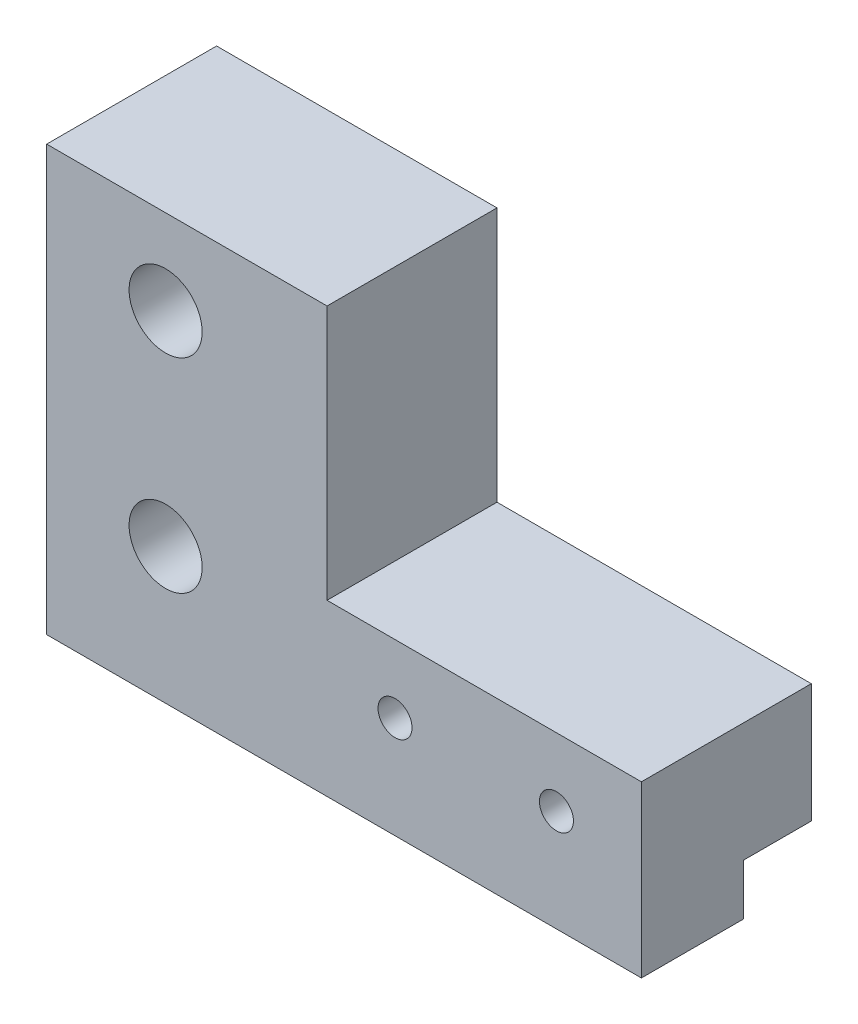
SolidWorks part; units mm, degrees
ref_plane "Front Plane" through (0, 0, 0) normal (0, 0, 1) x (1, 0, 0)
ref_plane "Top Plane" through (0, 0, 0) normal (0, 1, 0) x (1, 0, 0)
ref_plane "Right Plane" through (0, 0, 0) normal (1, 0, 0) x (0, 0, -1)
sketch "Sketch1" plane through (0, 0, 0) normal (0, 0, 1) x (1, 0, 0)
  line L0 (21, 5) -> (37.5, 5)
  line L1 (-37.5, 5) -> (-21, 5)
  line L2 (-37.5, 5) -> (-37.5, -20)
  line L3 (-37.5, -20) -> (37.5, -20)
  line L4 (37.5, 5) -> (37.5, -20)
  line L5 (-21, 5) -> (21, 5) construction
  line L6 (-21, 5) -> (-21, -10)
  line L7 (-21, -10) -> (21, -10)
  line L8 (21, 5) -> (21, -10)
  line L9 (30.5, -12) -> (30.5, 0) construction
  line L10 (30.5, 0) -> (-30.5, 0) construction
  line L11 (-30.5, 0) -> (-30.5, -12) construction
  line L12 (-30.5, -12) -> (30.5, -12) construction
  line L13 (-30.5, 0) -> (30.5, -12) construction
  line L14 (0, -10) -> (0, 0) construction
  circle A0 centre (-30.5, 0) radius 2.15
  circle A1 centre (-30.5, -12) radius 2.15
  circle A2 centre (30.5, 0) radius 2.15
  circle A3 centre (30.5, -12) radius 2.15
  dimension "D3" = 4.3
  dimension "D1" = 61
  dimension "D2" = 12
  dimension "D4" = 5
  dimension "D5" = 75
  dimension "D6" = 42
  dimension "D7" = 10
  dimension "D8" = 10
extrude "Boss-Extrude1" add sketch "Sketch1" along normal blind 10
sketch "Sketch3" plane through (0, 0, 0) normal (0, 0, -1) x (-1, 0, 0)
  line L0 (37.5, 5) -> (37.5, -20) construction
  line L1 (-37.5, -20) -> (37.5, -20)
  line L2 (-37.5, -20) -> (-37.5, -17)
  line L3 (-37.5, -17) -> (37.5, -17)
  line L4 (37.5, -20) -> (37.5, -17)
  circle A0 centre (30.5, -12) radius 2.15 construction
  dimension "D1" = 5
extrude "Cut-Extrude1" cut sketch "Sketch3" against normal blind 4
sketch "Sketch4" plane through (0, 0, 10) normal (0, 0, 1) x (1, 0, 0)
  line L0 (-37.5, -20) -> (37.5, -20) construction
  line L1 (37.5, 5) -> (-2.5, 5)
  line L2 (37.5, 5) -> (37.5, -20)
  line L3 (37.5, -20) -> (-2.5, -20)
  line L4 (-2.5, 5) -> (-2.5, -20)
  dimension "D1" = 40
extrude "Cut-Extrude2" cut sketch "Sketch4" against normal through all
sketch "Sketch5" plane through (0, 0, 10) normal (0, 0, 1) x (1, 0, 0)
  line L0 (-17, -14) -> (-7.5, -14) construction
  line L1 (-2.5, -10) -> (-21, -10) construction
  line L2 (-2.5, -10) -> (-2.5, -20) construction
  circle A0 centre (-7.5, -14) radius 1
  circle A1 centre (-17, -14) radius 1
  dimension "D1" = 2
  dimension "D3" = 5
  dimension "D2" = 4
  dimension "D4" = 9.5
extrude "Cut-Extrude3" cut sketch "Sketch5" against normal through all
